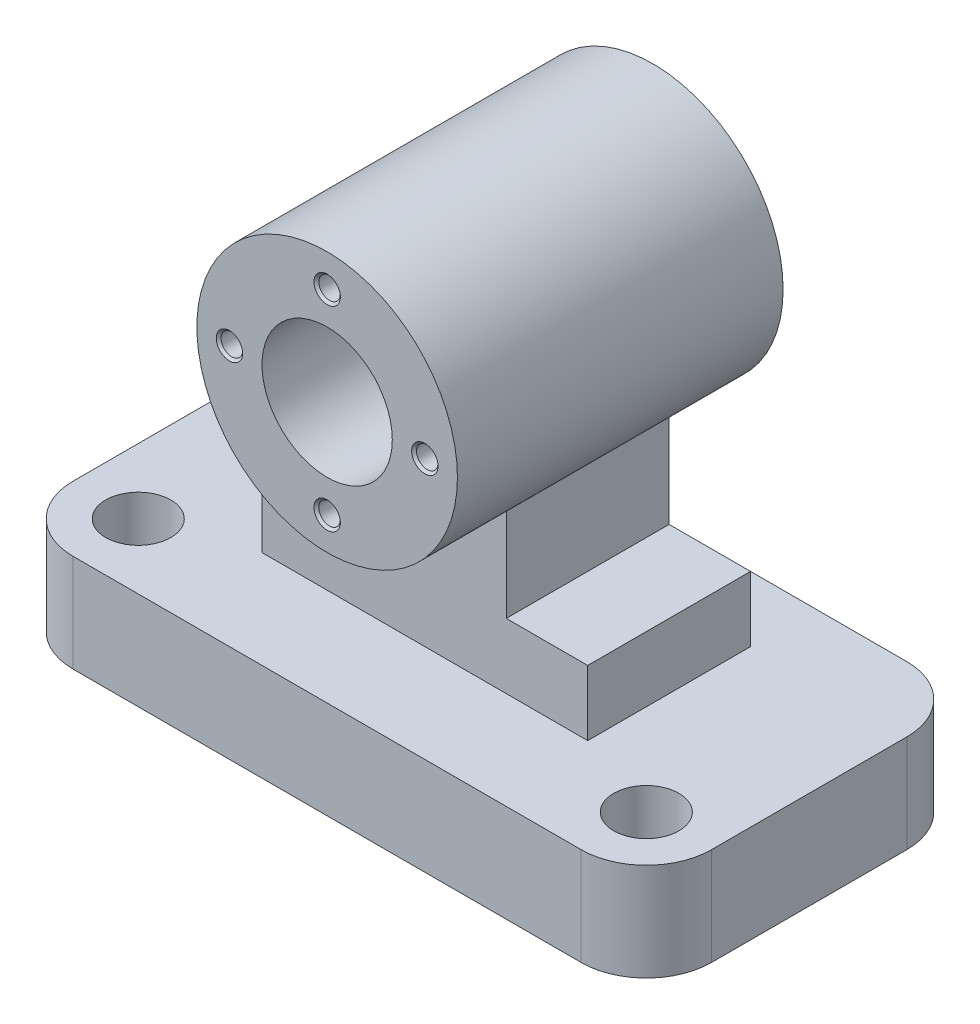
SolidWorks part; units mm, degrees
ref_plane "정면" through (0, 0, 0) normal (0, 0, 1) x (1, 0, 0)
ref_plane "윗면" through (0, 0, 0) normal (0, 1, 0) x (1, 0, 0)
ref_plane "우측면" through (0, 0, 0) normal (1, 0, 0) x (0, 0, -1)
sketch "스케치1" plane through (0, 0, 0) normal (0, 0, 1) x (1, 0, 0)
  line L1 (-49, -20.0074) -> (49, -20.0074)
  line L2 (-49, -20.0074) -> (-49, -35.0074)
  line L3 (-49, -35.0074) -> (49, -35.0074)
  line L4 (49, -20.0074) -> (49, -35.0074)
  line L5 (-49, -20.0074) -> (49, -35.0074) construction
  line L6 (-49, -35.0074) -> (49, -20.0074) construction
  point P0 (0, -27.5074)
  point P5 (0, 0)
  dimension "D1" = 15
  dimension "D2" = 98
extrude "보스-돌출1" add sketch "스케치1" along normal blind 50
sketch "스케치2" plane through (0, 0, 50) normal (0, 0, 1) x (1, 0, 0)
  line L0 (-49, -35.0074) -> (49, -35.0074) construction
  circle A0 centre (0, 19.9926) radius 10
  circle A1 centre (0, 19.9926) radius 20
  dimension "D1" = 20
  dimension "D2" = 40
  dimension "D3" = 55
extrude "보스-돌출2" add sketch "스케치2" against normal blind 50 separate body
sketch "스케치4" plane through (0, 0, 0) normal (1, 0, 0) x (0, 0, -1)
  line L0 (-50, -20.0074) -> (0, -20.0074) construction
  line L1 (-35, 4.3382) -> (-10, 4.3382)
  line L2 (-35, 4.3382) -> (-35, -20.0074)
  line L3 (-35, -20.0074) -> (-10, -20.0074)
  line L4 (-10, 4.3382) -> (-10, -20.0074)
  line L5 (-35, 4.3382) -> (-10, -20.0074) construction
  line L6 (-35, -20.0074) -> (-10, 4.3382) construction
  point P0 (-22.5, -7.8346)
  dimension "D1" = 35
  dimension "D2" = 10
extrude "보스-돌출3" add sketch "스케치4" against normal mid plane 25
sketch "스케치6" plane through (0, 0, 0) normal (0, 0, 1) x (1, 0, 0)
  line L0 (18.722, 27.0273) -> (39, -20.0074)
  line L1 (49, -20.0074) -> (-49, -20.0074) construction
  line L2 (-19.0873, 25.9656) -> (-39, -20.0074)
  line L3 (-39, -20.0074) -> (-12.5, -20.0074)
  line L4 (-12.5, -20.0074) -> (-12.5, 4.3382)
  line L5 (-12.5, 4.3382) -> (-19.0873, 25.9656)
  line L6 (39, -20.0074) -> (12.5, -20.0074)
  line L7 (12.5, -20.0074) -> (12.4475, 4.3382)
  line L8 (12.4475, 4.3382) -> (18.722, 27.0273)
  circle A0 centre (0, 19.9926) radius 20 construction
  circle A1 centre (0, 19.9926) radius 20 construction
  dimension "D1" = 39
  dimension "D2" = 39
fillet "필렛1" radius 10 4 edges at (-49, -27.5074, 0) (49, -27.5074, 0) (49, -27.5074, 50) (-49, -27.5074, 50)
sketch "스케치7" plane through (0, -20.0074, 0) normal (0, 1, 0) x (1, 0, 0)
  circle A0 centre (-39, -40) radius 5
  circle A1 centre (39, -40) radius 5
  dimension "D1" = 10
  dimension "D2" = 10
extrude "컷-돌출1" cut sketch "스케치7" against normal blind 25
sketch "스케치9" plane through (0, 0, 50) normal (0, 0, 1) x (1, 0, 0)
  line L1 (-31.5701, 19.9926) -> (34.9635, 19.9926) construction
  line L2 (0, 19.9926) -> (0, 48.4063) construction
  line L3 (0, 48.4063) -> (0, -6.3718) construction
  point P4 (0, 34.9926)
  point P8 (-15, 19.9926)
  point P9 (15, 19.9926)
  point P10 (0, 4.9926)
hole_wizard "M4 나사 구멍1" positions "3D스케치2" profile "스케치10" tap size "M4" standard "KS" end condition through all
sketch3d "3D스케치2"
  point P0 (0, 34.9926, 50)
  point P3 (-15, 19.9926, 50)
  point P6 (15, 19.9926, 50)
  point P9 (0, 4.9926, 50)
sketch "스케치10" plane through (0, 34.9926, 50) normal (1, 0, 0) x (0, -1, 0)
  line L0 (0, 0) -> (0, 50)
  line L1 (0, 50) -> (1.65, 50)
  line L2 (1.65, 50) -> (1.65, 0.3621)
  line L3 (1.65, 0.3621) -> (2.025, 0)
  line L5 (2.025, 0) -> (0, 0)
  line L6 (-1.65, 0.3621) -> (-2.025, 0) construction
  line L11 (0, -6.35) -> (0, 107.95) construction
  dimension "관통 탭 드릴 지름" = 3.3
  dimension "관통 탭 드릴 깊이" = 50
  dimension "표면 카운터싱크 지름" = 4.05
  dimension "표면 카운터싱크 각도" = 92
cosmetic thread "구멍 나사산1" parameters "D2"=4
cosmetic thread "구멍 나사산2" parameters "D2"=4
cosmetic thread "구멍 나사산3" parameters "D2"=4
cosmetic thread "구멍 나사산4" parameters "D2"=4
sketch "스케치12" plane through (0, 0, 35) normal (0, 0, 1) x (1, 0, 0)
  line L0 (39, -20.0074) -> (-39, -20.0074) construction
  line L1 (-25, -10.0074) -> (25, -10.0074)
  line L2 (-25, -10.0074) -> (-25, -20.0074)
  line L3 (-25, -20.0074) -> (25, -20.0074)
  line L4 (25, -10.0074) -> (25, -20.0074)
  point P0 (0, -15.0074)
  dimension "D1" = 10
  dimension "D2" = 25
  dimension "D3" = 50
extrude "보스-돌출4" add sketch "스케치12" against normal blind 25
